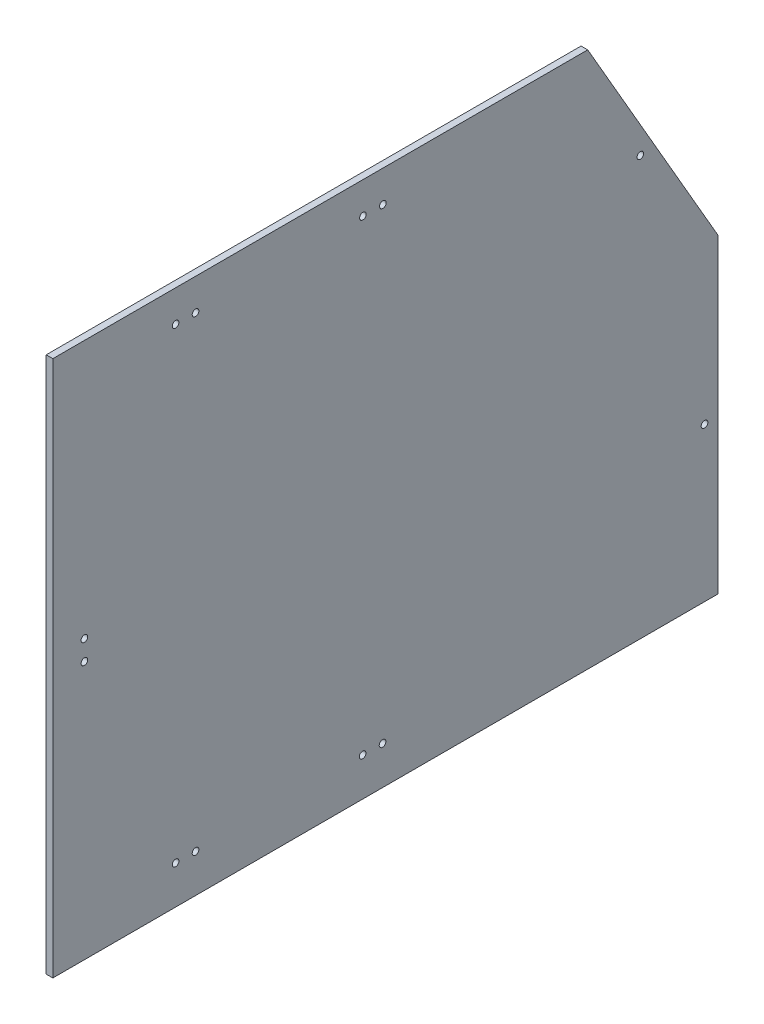
SolidWorks part; units mm, degrees
ref_plane "Front Plane" through (0, 0, 0) normal (0, 0, 1) x (1, 0, 0)
ref_plane "Top Plane" through (0, 0, 0) normal (0, 1, 0) x (1, 0, 0)
ref_plane "Right Plane" through (0, 0, 0) normal (1, 0, 0) x (0, 0, -1)
sketch "Sketch1" plane through (0, 0, 0) normal (1, 0, 0) x (0, 0, -1)
  line L0 (-213.2484, 113.1802) -> (-213.2484, -128.7898)
  line L1 (-213.2484, -128.7898) -> (86.7516, -128.7898)
  line L2 (86.7516, -128.7898) -> (86.7516, 11.5102)
  line L3 (86.7516, 11.5102) -> (28.0524, 113.1802)
  line L4 (28.0524, 113.1802) -> (-213.2484, 113.1802)
  line L5 (86.7516, 11.5102) -> (86.7516, 156.8494) construction
  dimension "D1" = 241.97
  dimension "D2" = 300
  dimension "D3" = 330
  dimension "D4" = 140.3
  dimension "D5" = 117.3984
extrude "Boss-Extrude1" add sketch "Sketch1" along normal blind 3
sketch "Sketch2" plane through (3, 0, 0) normal (1, 0, 0) x (0, 0, -1)
  line L0 (28.0524, 113.1802) -> (-213.2484, 113.1802)
  line L1 (-213.2484, 113.1802) -> (-213.2484, -128.7898)
  line L2 (-213.2484, -128.7898) -> (86.7516, -128.7898)
  line L3 (86.7516, -128.7898) -> (86.7516, 11.5102)
  line L4 (86.7516, 11.5102) -> (28.0524, 113.1802)
  line L5 (-63.5022, -105.7898) -> (-74.5022, -105.7898)
  line L6 (-76.5022, -107.7898) -> (-76.5022, -122.7898)
  line L7 (-76.5022, -122.7898) -> (-61.5022, -122.7898)
  line L8 (-61.5022, -122.7898) -> (-61.5022, -107.7898)
  line L9 (-147.8671, -105.7898) -> (-158.8671, -105.7898)
  line L10 (-160.8671, -107.7898) -> (-160.8671, -122.7898)
  line L11 (-160.8671, -122.7898) -> (-145.8671, -122.7898)
  line L12 (-145.8671, -122.7898) -> (-145.8671, -107.7898)
  line L13 (-153.3671, -105.7898) -> (-153.3671, -125.0598) construction
  line L14 (-76.5022, -107.7898) -> (-76.5022, -122.7898)
  line L15 (-63.5022, -105.7898) -> (-74.5022, -105.7898)
  line L16 (-76.5022, -122.7898) -> (-61.5022, -122.7898)
  line L17 (-61.5022, -122.7898) -> (-61.5022, -107.7898)
  line L18 (28.0524, 113.1802) -> (-213.2484, 113.1802)
  line L19 (-213.2484, 113.1802) -> (-213.2484, -128.7898)
  line L20 (-213.2484, -128.7898) -> (86.7516, -128.7898)
  line L21 (86.7516, -128.7898) -> (86.7516, 11.5102)
  line L22 (86.7516, 11.5102) -> (28.0524, 113.1802)
  line L23 (28.0524, 113.1802) -> (-213.2484, 113.1802)
  line L24 (-213.2484, 113.1802) -> (-213.2484, -128.7898)
  line L25 (-213.2484, -128.7898) -> (86.7516, -128.7898)
  line L26 (86.7516, -128.7898) -> (86.7516, 11.5102)
  line L27 (86.7516, 11.5102) -> (28.0524, 113.1802)
  line L28 (-153.3671, -122.7898) -> (-153.3671, -128.7898)
  line L29 (-210.6234, -15.3048) -> (-192.2484, -15.3048)
  line L30 (-192.2484, -0.3048) -> (-210.6234, -0.3048)
  line L31 (-190.2484, -13.3048) -> (-190.2484, -2.3048)
  line L32 (-210.6234, -7.8048) -> (-213.2484, -7.8048)
  line L33 (-210.6234, -0.3048) -> (-210.6234, -15.3048)
  line L34 (-213.2484, -7.8048) -> (93.9942, -7.8048) construction
  arc A0 (-74.5022, -105.7898) -> (-76.5022, -107.7898) centre (-74.5022, -107.7898) ccw
  arc A1 (-61.5022, -107.7898) -> (-63.5022, -105.7898) centre (-63.5022, -107.7898) ccw
  arc A2 (-158.8671, -105.7898) -> (-160.8671, -107.7898) centre (-158.8671, -107.7898) ccw
  arc A3 (-145.8671, -107.7898) -> (-147.8671, -105.7898) centre (-147.8671, -107.7898) ccw
  circle A4 centre (-157.8671, -111.5369) radius 1.5
  circle A5 centre (-64.3549, 98.9272) radius 1.5
  circle A6 centre (-73.3549, 98.9272) radius 1.5
  circle A7 centre (-148.8671, 98.9272) radius 1.5
  circle A8 centre (-157.8671, 98.9272) radius 1.5
  circle A9 centre (-148.8671, -111.5369) radius 1.5
  arc A10 (-61.5022, -107.7898) -> (-63.5022, -105.7898) centre (-63.5022, -107.7898) ccw
  circle A11 centre (-64.5022, -111.5369) radius 1.5
  circle A12 centre (-73.5022, -111.5369) radius 1.5
  arc A13 (-74.5022, -105.7898) -> (-76.5022, -107.7898) centre (-74.5022, -107.7898) ccw
  circle A14 centre (-198.9955, -3.3048) radius 1.5
  arc A15 (-190.2484, -2.3048) -> (-192.2484, -0.3048) centre (-192.2484, -2.3048) ccw
  circle A16 centre (-198.9955, -12.3048) radius 1.5
  arc A17 (-192.2484, -15.3048) -> (-190.2484, -13.3048) centre (-192.2484, -13.3048) ccw
  dimension "D1" = 0
extrude "Cut-Extrude1" cut sketch "Sketch2" against normal blind 10 contours A4 | A9 | A12 | A11 | A5 | A6 | A7 | A8 | A14 | A16
sketch "Sketch3" plane through (3, 0, 0) normal (1, 0, 0) x (0, 0, -1)
  line L0 (86.7516, 11.5102) -> (28.0524, 113.1802) construction
  line L1 (86.7516, 11.5102) -> (28.0524, 113.1802)
  line L2 (86.7516, -128.7898) -> (86.7516, 11.5102) construction
  line L3 (86.7516, -128.7898) -> (86.7516, 11.5102)
  line L4 (80.7516, -128.7898) -> (80.7516, 9.9025)
  line L5 (80.7516, 9.9025) -> (22.8562, 110.1802)
  circle A0 centre (-198.9955, -3.3048) radius 1.5 construction
  circle A1 centre (-198.9955, -3.3048) radius 1.5
  circle A2 centre (51.8039, 60.0413) radius 1.5
  circle A3 centre (80.7516, -59.4437) radius 1.5
  dimension "D1" = 6
extrude "Cut-Extrude2" cut sketch "Sketch3" against normal blind 10 contours L4 A3 | L4 A3 | L5 A2 | L5 A2
